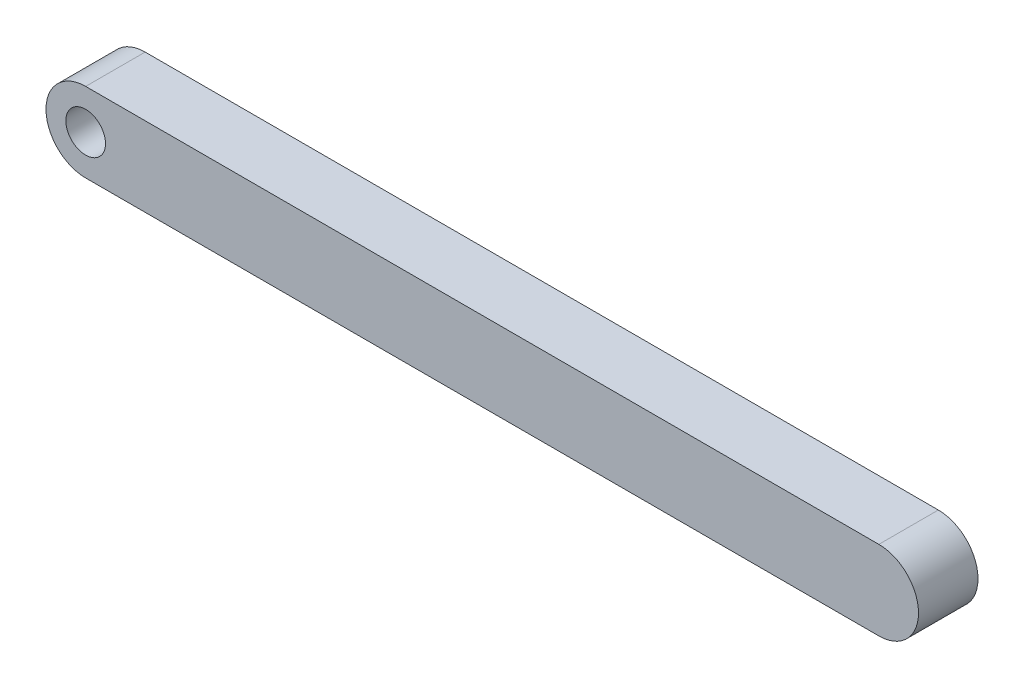
SolidWorks part; units mm, degrees
ref_plane "前视基准面" through (0, 0, 0) normal (0, 0, 1) x (1, 0, 0)
ref_plane "上视基准面" through (0, 0, 0) normal (0, 1, 0) x (1, 0, 0)
ref_plane "右视基准面" through (0, 0, 0) normal (1, 0, 0) x (0, 0, -1)
sketch "草图1" plane through (0, 0, 0) normal (0, 0, 1) x (1, 0, 0)
  line L0 (0, 0) -> (40, 0) construction
  line L2 (0, 2) -> (40, 2)
  line L3 (0, -2) -> (40, -2)
  arc A0 (0, 2) -> (0, -2) centre (0, 0) ccw
  arc A1 (40, -2) -> (40, 2) centre (40, 0) ccw
  circle A2 centre (0, 0) radius 1
  point P5 (20, 0)
  dimension "D3" = 2
  dimension "D1" = 4
  dimension "D2" = 40
extrude "凸台-拉伸1" add sketch "草图1" along normal mid plane 3
